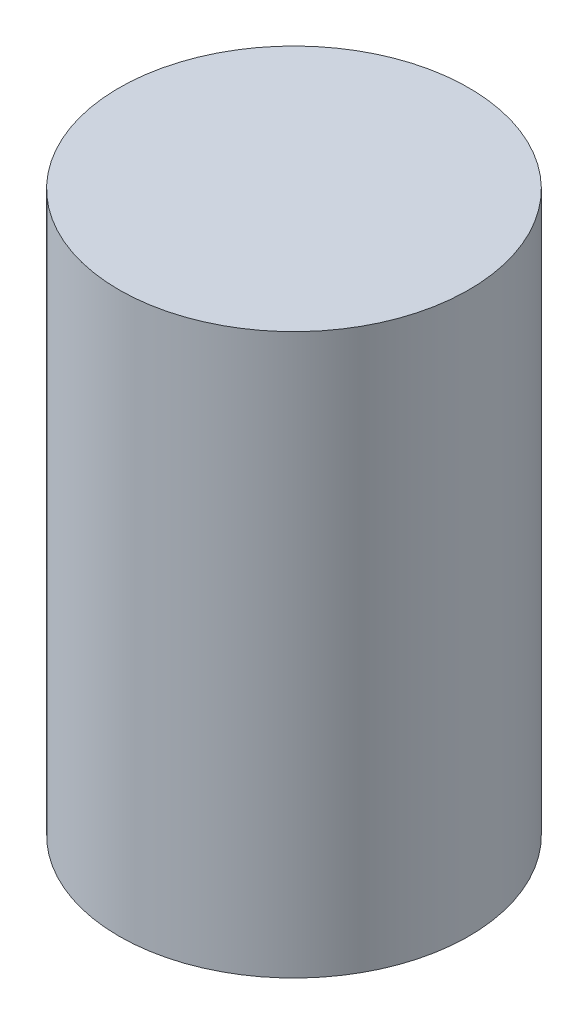
SolidWorks part; units mm, degrees
ref_plane "Front Plane" through (0, 0, 0) normal (0, 0, 1) x (1, 0, 0)
ref_plane "Top Plane" through (0, 0, 0) normal (0, 1, 0) x (1, 0, 0)
ref_plane "Right Plane" through (0, 0, 0) normal (1, 0, 0) x (0, 0, -1)
sketch "Sketch1" plane through (0, 0, 0) normal (0, 1, 0) x (1, 0, 0)
  circle A0 centre (0, 0) radius 37.5
  dimension "D1" = 75
extrude "Boss-Extrude1" add sketch "Sketch1" along normal blind 120
